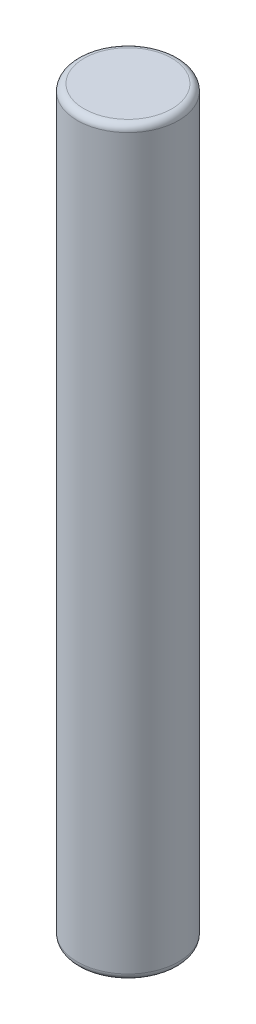
SolidWorks part; units mm, degrees
ref_plane "Front Plane" through (0, 0, 0) normal (0, 0, 1) x (1, 0, 0)
ref_plane "Top Plane" through (0, 0, 0) normal (0, 1, 0) x (1, 0, 0)
ref_plane "Right Plane" through (0, 0, 0) normal (1, 0, 0) x (0, 0, -1)
sketch "Sketch1" plane through (0, 0, 0) normal (0, 1, 0) x (1, 0, 0)
  circle A0 centre (0, 0) radius 15
  dimension "D1" = 30
extrude "Boss-Extrude1" add sketch "Sketch1" along normal mid plane 220
fillet "Fillet1" radius 2 2 edges at (0, -110, 15) (0, 110, 15)
